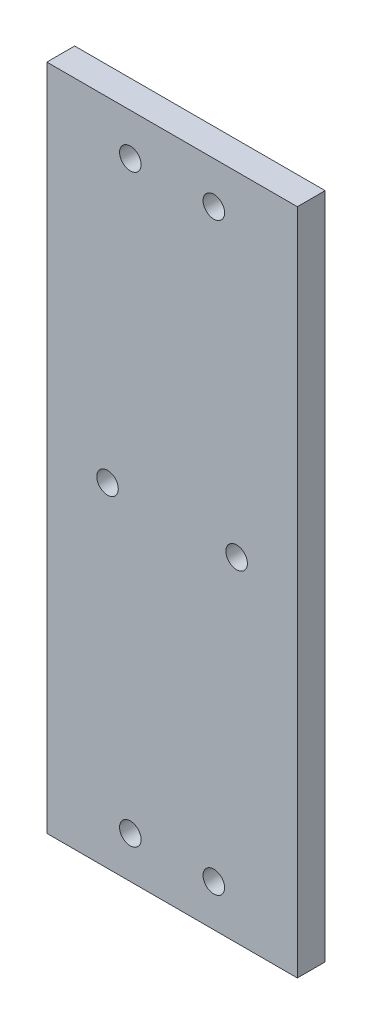
SolidWorks part; units mm, degrees
material "Pine"
ref_plane "Front Plane" through (0, 0, 0) normal (0, 0, 1) x (1, 0, 0)
ref_plane "Top Plane" through (0, 0, 0) normal (0, 1, 0) x (1, 0, 0)
ref_plane "Right Plane" through (0, 0, 0) normal (1, 0, 0) x (0, 0, -1)
sketch "Sketch2" plane through (0, 0, 0) normal (0, 0, 1) x (1, 0, 0)
  line L1 (0, 0) -> (57.15, 0)
  line L2 (0, 0) -> (0, 152.4)
  line L3 (0, 152.4) -> (57.15, 152.4)
  line L4 (57.15, 0) -> (57.15, 152.4)
  dimension "D1" = 57.15
  dimension "D2" = 152.4
extrude "Boss-Extrude1" add sketch "Sketch2" along normal blind 6.35
hole_wizard "#8 Clearance Hole1" positions "Sketch5" profile "Sketch6" hole size "#8" standard "ANSI Inch"
sketch "Sketch5" plane through (0, 0, 6.35) normal (0, 0, 1) x (1, 0, 0)
  line L0 (19.05, 9.525) -> (38.1, 9.525)
  line L2 (0, 0) -> (57.15, 0) construction
  line L3 (57.15, 152.4) -> (0, 152.4) construction
  line L4 (13.843, 76.2) -> (43.307, 76.2)
  point P0 (19.05, 9.525)
  point P2 (38.1, 9.525)
  point P12 (28.575, 0)
  point P13 (28.575, 9.525)
  point P14 (19.05, 142.875)
  point P16 (38.1, 142.875)
  point P23 (13.843, 76.2)
  point P25 (43.307, 76.2)
  point P32 (28.575, 76.2)
  dimension "D1" = 9.525
  dimension "D2" = 19.05
  dimension "D3" = 9.525
  dimension "D4" = 29.464
  dimension "D5" = 76.2
sketch "Sketch6" plane through (19.05, 9.525, 6.35) normal (1, 0, 0) x (0, -1, 0)
  line L0 (0, 0) -> (0, 10.668)
  line L1 (0, 10.668) -> (2.4574, 9.1914)
  line L2 (2.4574, 9.1914) -> (2.4574, 0)
  line L5 (2.4574, 0) -> (0, 0)
  line L10 (0, 10.668) -> (-2.4575, 9.1914) construction
  line L11 (0, -6.35) -> (0, 107.95) construction
  dimension "Hole Dia." = 4.9149
  dimension "Hole Depth" = 10.668
  dimension "Drill Angle" = 118
